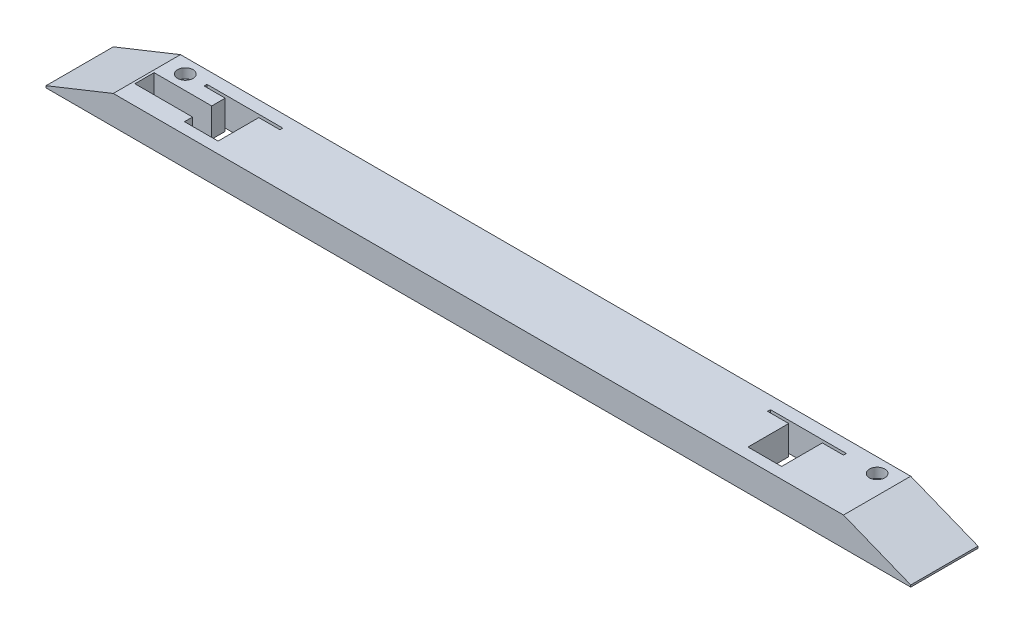
SolidWorks part; units mm, degrees
ref_plane "Front Plane" through (0, 0, 0) normal (0, 0, 1) x (1, 0, 0)
ref_plane "Top Plane" through (0, 0, 0) normal (0, 1, 0) x (1, 0, 0)
ref_plane "Right Plane" through (0, 0, 0) normal (1, 0, 0) x (0, 0, -1)
ref_plane "Plane1" through (0, 0, 35) normal (0, 0, 1) x (1, 0, 0)
sketch "Sketch1" plane through (0, 0, 35) normal (0, 0, 1) x (1, 0, 0)
  line L0 (0, 0) -> (450, 0)
  line L1 (450, 0) -> (450, 1)
  line L2 (450, 1) -> (415, 15)
  line L3 (415, 15) -> (35, 15)
  line L4 (35, 15) -> (0, 1)
  line L5 (0, 1) -> (0, 0)
extrude "Boss-Extrude1" add sketch "Sketch1" against normal blind 35
sketch "Sketch2" plane through (0, 15, 0) normal (0, 1, 0) x (-1, 0, 0)
  line L0 (-359.5, 8) -> (-359.5, 29.2)
  line L1 (-359.5, 29.2) -> (-377, 29.2)
  line L2 (-377, 29.2) -> (-377, 8)
  line L3 (-377, 8) -> (-388, 8)
  line L4 (-388, 8) -> (-388, 6.5)
  line L5 (-388, 6.5) -> (-348.5, 6.5)
  line L6 (-348.5, 6.5) -> (-348.5, 8)
  line L7 (-348.5, 8) -> (-359.5, 8)
extrude "Cut-Extrude1" cut sketch "Sketch2" against normal through all
sketch "Sketch3" plane through (0, 0, 0) normal (0, -1, 0) x (1, 0, 0)
  line L0 (66.25, 15) -> (66.25, 8)
  line L1 (66.25, 8) -> (55.25, 8)
  line L2 (55.25, 8) -> (55.25, 6.5)
  line L3 (55.25, 6.5) -> (94.75, 6.5)
  line L4 (94.75, 6.5) -> (94.75, 8)
  line L5 (94.75, 8) -> (83.75, 8)
  line L6 (83.75, 8) -> (83.75, 29.2)
  line L7 (83.75, 29.2) -> (66.25, 29.2)
  line L8 (66.25, 29.2) -> (66.25, 25)
  line L9 (66.25, 25) -> (36.25, 25)
  line L10 (36.25, 25) -> (36.25, 15)
  line L11 (36.25, 15) -> (66.25, 15)
extrude "Cut-Extrude2" cut sketch "Sketch3" against normal through all
hole_wizard "M8x1.0 Tapped Hole1" positions "Sketch5" profile "Sketch4" tap size "M8x1.0" standard "ANSI Metric"
sketch "Sketch5" plane through (0, 15, 0) normal (0, 1, 0) x (1, 0, 0)
  point P0 (45, -7.5)
  point P1 (405, -7.5)
sketch "Sketch4" plane through (45, 15, 7.5) normal (1, 0, 0) x (0, 0, 1)
  line L0 (0, 0) -> (0, 15)
  line L1 (0, 15) -> (2.5, 15)
  line L3 (2.5, 15) -> (2.5, 5)
  line L4 (2.5, 5) -> (4, 5)
  line L5 (4, 5) -> (4, 0)
  line L7 (4, 0) -> (0, 0)
  line L11 (0, -6.35) -> (0, 107.95) construction
  dimension "Thru Tap Drill Dia." = 5
  dimension "Thru Tap Drill Depth" = 15
  dimension "Thread Major Dia." = 8
  dimension "Thread Depth" = 5
